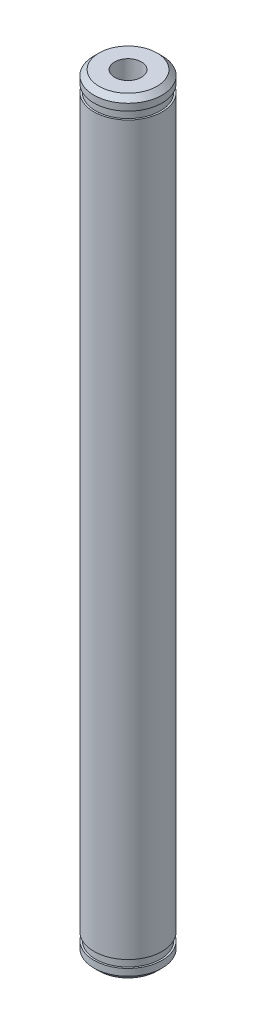
SolidWorks part; units mm, degrees
material "6061-T6 (SS)"
ref_plane "Front Plane" through (0, 0, 0) normal (0, 0, 1) x (1, 0, 0)
ref_plane "Top Plane" through (0, 0, 0) normal (0, 1, 0) x (1, 0, 0)
ref_plane "Right Plane" through (0, 0, 0) normal (1, 0, 0) x (0, 0, -1)
sketch "Sketch1" plane through (0, 0, 0) normal (0, 1, 0) x (1, 0, 0)
  circle A0 centre (0, 0) radius 4
  dimension "D1" = 8
extrude "Boss-Extrude1" add sketch "Sketch1" along normal blind 90
chamfer "Chamfer1" distance 0.6 angle 45 2 edges at (0, 90, 4) (0, 0, 4)
sketch "Sketch2" plane through (0, 0, 0) normal (0, -1, 0) x (1, 0, 0)
  circle A0 centre (0, 0) radius 3.8
  circle A1 centre (0, 0) radius 4 construction
  circle A2 centre (0, 0) radius 4
  dimension "D1" = 7.6
extrude "Cut-Extrude1" cut sketch "Sketch2" against normal blind 0.9 from offset 1.4 offset against normal yes
ref_plane "Plane1" through (0, 45, 0) normal (0, -1, 0) x (-1, 0, 0)
hole_wizard "Tap Drill for M3 Helicoil1" positions "Sketch5" profile "Sketch4" hole size "M3x0.5" standard "DIN"
sketch "Sketch5" plane through (0, 90, 0) normal (0, 1, 0) x (1, 0, 0)
  point P0 (0, 0)
sketch "Sketch4" plane through (0, 90, 0) normal (1, 0, 0) x (0, 0, 1)
  line L0 (0, 0) -> (0, 6)
  line L1 (0, 6) -> (1.575, 6)
  line L2 (1.575, 6) -> (1.575, 0)
  line L5 (1.575, 0) -> (0, 0)
  line L10 (0, 6) -> (-1.575, 6) construction
  line L11 (0, -6.35) -> (0, 107.95) construction
  dimension "Hole Dia." = 3.15
  dimension "Hole Depth" = 6
  dimension "Drill Angle" = 180
mirror "Mirror1" about plane through (0, 45, 0) normal (0, -1, 0) of "Cut-Extrude1"
